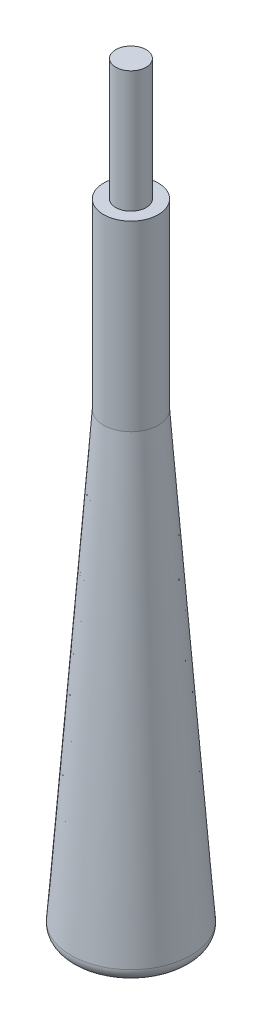
SolidWorks part; units mm, degrees
material "Rubber"
ref_plane "Front Plane" through (0, 0, 0) normal (0, 0, 1) x (1, 0, 0)
ref_plane "Top Plane" through (0, 0, 0) normal (0, 1, 0) x (1, 0, 0)
ref_plane "Right Plane" through (0, 0, 0) normal (1, 0, 0) x (0, 0, -1)
sketch "Sketch1" plane through (0, 0, 0) normal (0, 1, 0) x (1, 0, 0)
  circle A0 centre (0, 0) radius 2.5
extrude "Boss-Extrude1" add sketch "Sketch1" along normal blind 20
cosmetic thread "Cosmetic Thread1" parameters "D2"=4
sketch "Sketch2" plane through (0, 0, 0) normal (0, -1, 0) x (1, 0, 0)
  circle A0 centre (0, 0) radius 4.5
extrude "Boss-Extrude2" add sketch "Sketch2" along normal blind 30
sketch "Sketch3" plane through (0, 0, 0) normal (0, 0, 1) x (1, 0, 0)
  line L0 (0, -30) -> (0, -125.0766) construction
  line L1 (-4.5, -30) -> (4.5, -30) construction
  line L4 (10, -105) -> (4.5, -30)
  line L5 (10, -105) -> (7.25, -105)
  line L6 (4.5, -30) -> (2.5, -30)
  line L7 (2.5, -30) -> (7.25, -105)
  point P8 (0, -105)
revolve "Revolve1" add sketch "Sketch3" angle 360 about L0
fillet "Fillet1" radius 2 1 edges at (0, -105, 10)
